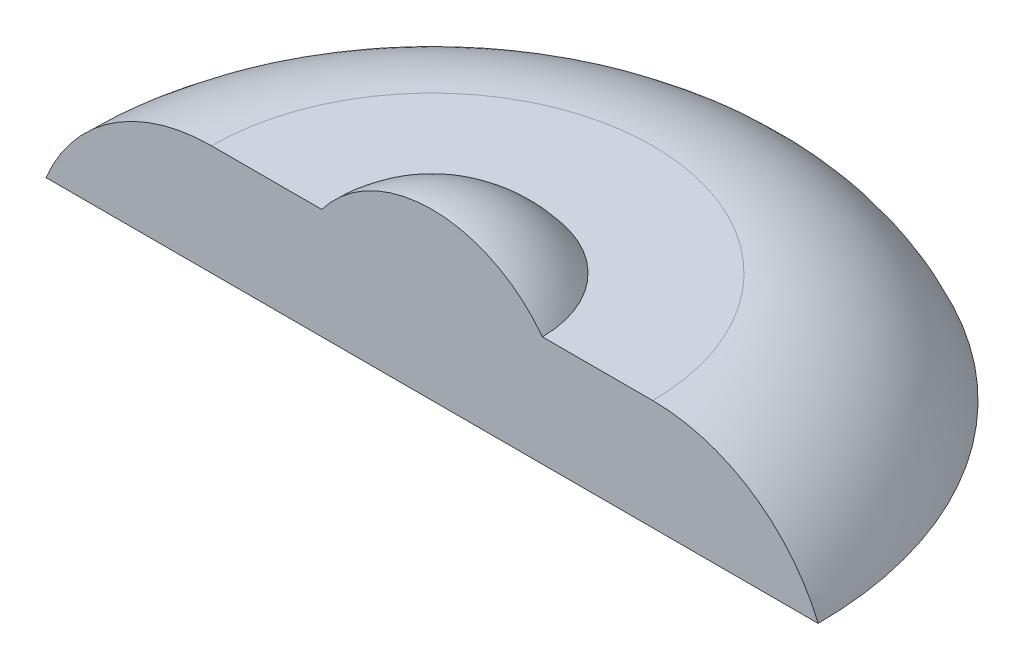
SolidWorks part; units mm, degrees
material "Glass"
ref_plane "Front Plane" through (0, 0, 0) normal (0, 0, 1) x (1, 0, 0)
ref_plane "Top Plane" through (0, 0, 0) normal (0, 1, 0) x (1, 0, 0)
ref_plane "Right Plane" through (0, 0, 0) normal (1, 0, 0) x (0, 0, -1)
sketch "Sketch2" plane through (0, 0, 0) normal (0, 0, 1) x (1, 0, 0)
  line L0 (0, 0) -> (0, 38.1)
  line L9 (25.4, 25.4) -> (50.8, 25.4)
  line L10 (88.9, 0) -> (0, 0)
  arc A0 (0, 38.1) -> (25.4, 25.4) centre (0, 6.35) cw
  arc A1 (50.8, 25.4) -> (88.9, 0) centre (50.8, -15.875) cw
  point P0 (0, 0)
  point P11 (50.8, 25.4)
  dimension "D7" = 41.275
  dimension "D9" = 31.75
  dimension "D1" = 88.9
  dimension "D2" = 90
  dimension "D3" = 38.1
  dimension "D4" = 0
  dimension "D6" = 12.7
revolve "Revolve2" add sketch "Sketch2" angle 180 about L0
